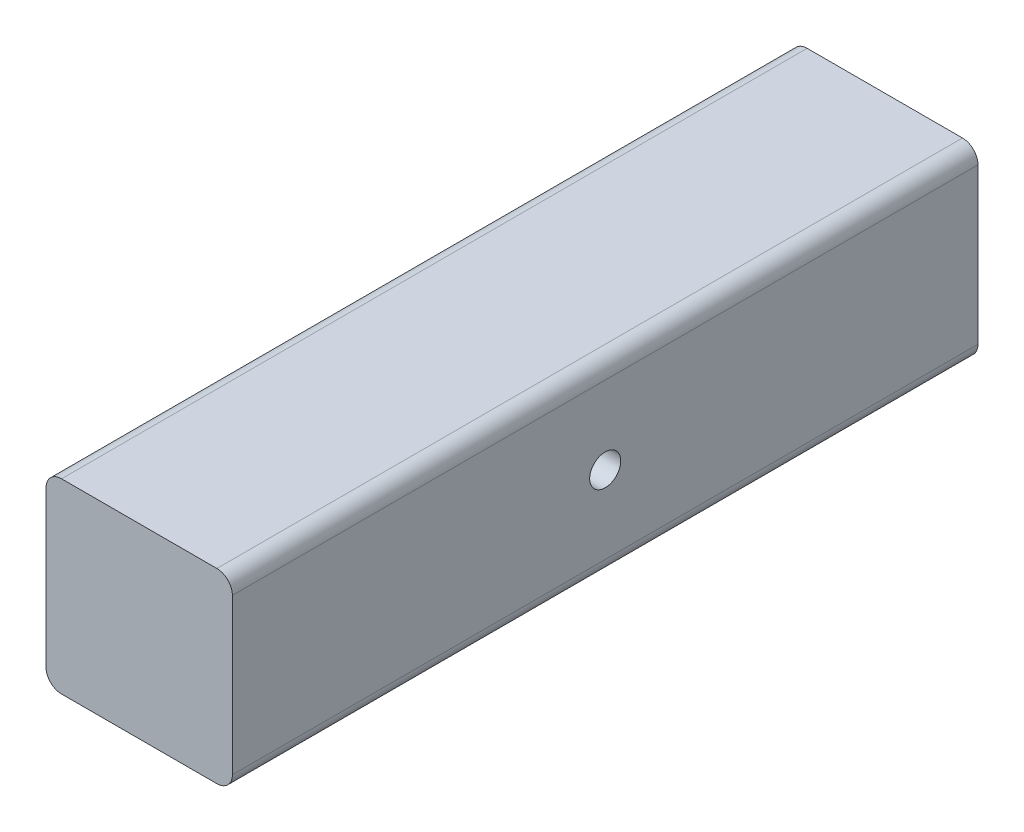
SolidWorks part; units mm, degrees
ref_plane "Front Plane" through (0, 0, 0) normal (0, 0, 1) x (1, 0, 0)
ref_plane "Top Plane" through (0, 0, 0) normal (0, 1, 0) x (1, 0, 0)
ref_plane "Right Plane" through (0, 0, 0) normal (1, 0, 0) x (0, 0, -1)
sketch "Sketch1" plane through (0, 0, 0) normal (0, 0, 1) x (1, 0, 0)
  line L1 (-19.05, -19.05) -> (19.05, -19.05)
  line L2 (-19.05, -19.05) -> (-19.05, 19.05)
  line L3 (-19.05, 19.05) -> (19.05, 19.05)
  line L4 (19.05, -19.05) -> (19.05, 19.05)
  line L5 (-19.05, -19.05) -> (19.05, 19.05) construction
  line L6 (-19.05, 19.05) -> (19.05, -19.05) construction
  point P0 (0, 0)
  dimension "D1" = 38.1
  dimension "D2" = 38.1
extrude "Boss-Extrude1" add sketch "Sketch1" along normal blind 152.4
fillet "Fillet1" radius 3.175 4 edges at (-19.05, 19.05, 76.2) (-19.05, -19.05, 76.2) (19.05, -19.05, 76.2) (19.05, 19.05, 76.2)
sketch "Sketch2" plane through (-19.05, 0, 0) normal (-1, 0, 0) x (0, 0, 1)
  line L1 (152.4, 15.875) -> (0, 15.875) construction
  line L2 (76.2, 15.875) -> (76.2, -15.875) construction
  line L3 (0, -15.875) -> (152.4, -15.875) construction
  circle A0 centre (76.2, 0) radius 3.175
  point P2 (0, 0)
  dimension "D1" = 6.35
extrude "Cut-Extrude1" cut sketch "Sketch2" against normal through all
